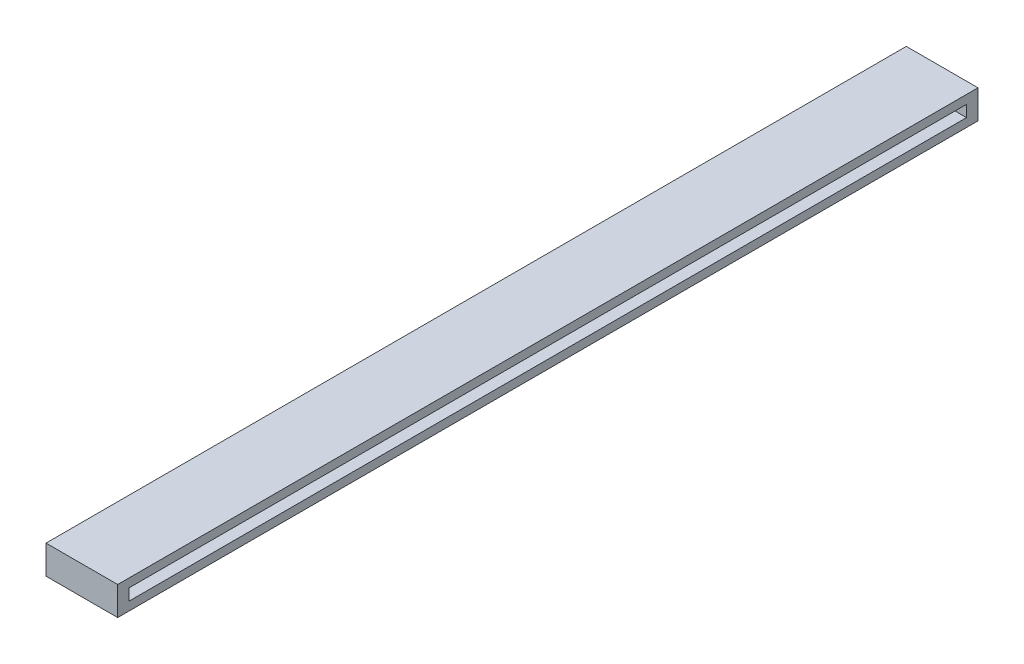
SolidWorks part; units mm, degrees
ref_plane "前视基准面" through (0, 0, 0) normal (0, 0, 1) x (1, 0, 0)
ref_plane "上视基准面" through (0, 0, 0) normal (0, 1, 0) x (1, 0, 0)
ref_plane "右视基准面" through (0, 0, 0) normal (1, 0, 0) x (0, 0, -1)
other "Configuration Table"
sketch "草图1" plane through (0, 0, 0) normal (0, 1, 0) x (1, 0, 0)
  line L1 (-62.3362, 84.2911) -> (-47.3362, 84.2911)
  line L2 (-62.3362, 84.2911) -> (-62.3362, -215.7089)
  line L3 (-62.3362, -215.7089) -> (-47.3362, -215.7089)
  line L4 (-47.3362, 84.2911) -> (-47.3362, -215.7089)
  dimension "D1" = 300
  dimension "D2" = 15
extrude "凸台-拉伸1" add sketch "草图1" along normal blind 4
sketch "草图2" plane through (-47.3362, 0, 0) normal (1, 0, 0) x (0, 0, -1)
  line L7 (-215.7089, 4) -> (-211.7089, 4)
  line L8 (-215.7089, 4) -> (-215.7089, 0)
  line L9 (-215.7089, 0) -> (-211.7089, 0)
  line L10 (-211.7089, 4) -> (-211.7089, 0)
  line L11 (-215.7089, 0) -> (84.2911, 0) construction
  line L13 (84.2911, 4) -> (80.2911, 4)
  line L14 (84.2911, 4) -> (84.2911, 0)
  line L15 (84.2911, 0) -> (80.2911, 0)
  line L16 (80.2911, 4) -> (80.2911, 0)
  dimension "D1" = 4
  dimension "D2" = 4
  dimension "D3" = 4
  dimension "D4" = 4
extrude "凸台-拉伸2" add sketch "草图2" along normal blind 10
sketch "草图3" plane through (0, 4, 0) normal (0, 1, 0) x (1, 0, 0)
  line L1 (-62.3362, 84.2911) -> (-37.3362, 84.2911)
  line L2 (-62.3362, 84.2911) -> (-62.3362, -215.7089)
  line L3 (-62.3362, -215.7089) -> (-37.3362, -215.7089)
  line L4 (-37.3362, 84.2911) -> (-37.3362, -215.7089)
  dimension "D1" = 300
  dimension "D2" = 25
extrude "凸台-拉伸3" add sketch "草图3" along normal blind 3
sketch "草图4" plane through (0, 0, 0) normal (0, -1, 0) x (1, 0, 0)
  line L1 (-62.3362, 215.7089) -> (-37.3362, 215.7089)
  line L2 (-62.3362, 215.7089) -> (-62.3362, -84.2911)
  line L3 (-62.3362, -84.2911) -> (-37.3362, -84.2911)
  line L4 (-37.3362, 215.7089) -> (-37.3362, -84.2911)
  dimension "D1" = 300
  dimension "D2" = 25
extrude "凸台-拉伸4" add sketch "草图4" along normal blind 3
